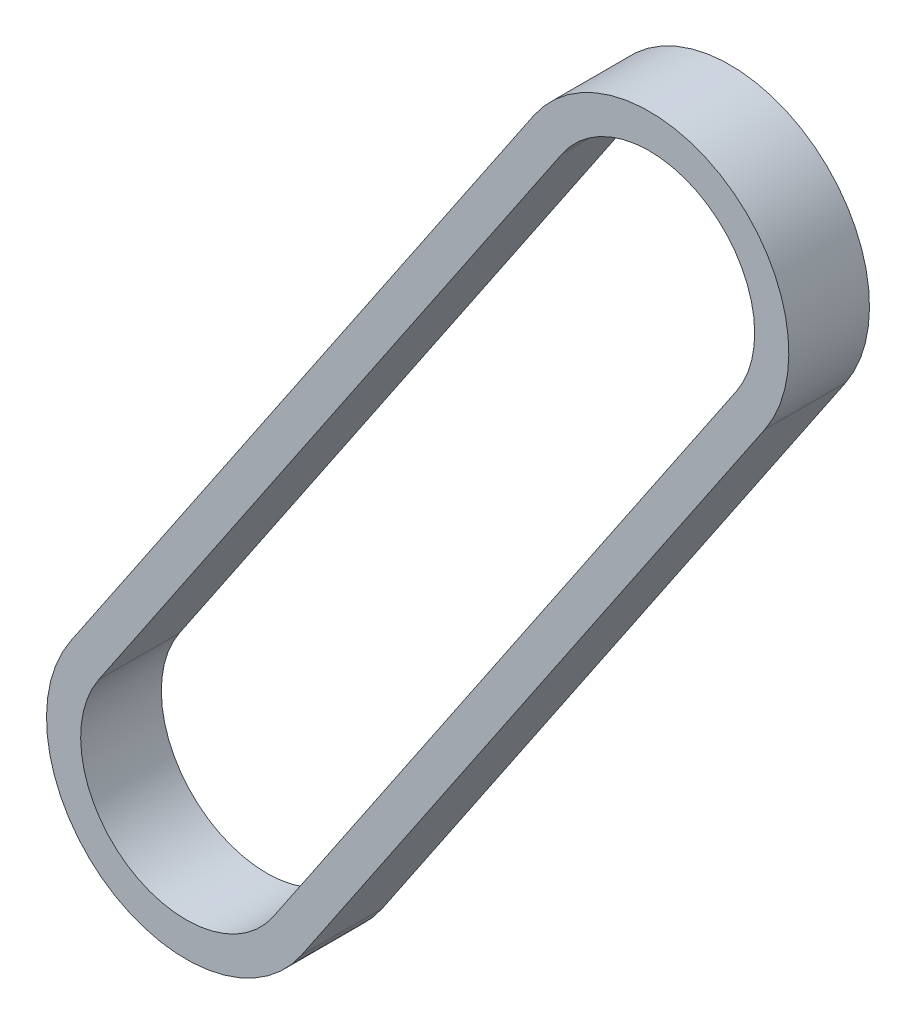
SolidWorks part; units mm, degrees
ref_plane "Front Plane" through (0, 0, 0) normal (0, 0, 1) x (1, 0, 0)
ref_plane "Top Plane" through (0, 0, 0) normal (0, 1, 0) x (1, 0, 0)
ref_plane "Right Plane" through (0, 0, 0) normal (1, 0, 0) x (0, 0, -1)
sketch "Sketch2" plane through (0, 0, 0) normal (0, 0, 1) x (1, 0, 0)
  line L0 (0, 0) -> (1, 0) construction
  line L1 (0, 0) -> (0, 1) construction
  line L2 (-63.158, -68.898) -> (-11.4682, 7.7354)
  line L3 (11.4682, -7.7354) -> (-40.2217, -84.3687)
  arc A0 (-40.2217, -84.3687) -> (-63.158, -68.898) centre (-51.6898, -76.6333) cw
  arc A1 (-11.4682, 7.7354) -> (11.4682, -7.7354) centre (0, 0) cw
extrude "Extrude-Thin1" add sketch "Sketch2" along normal mid plane 9 thin thin type two direction wall 1.73 second wall 2.08
equation "\"D1@Extrude-Thin1\"=9mm"
equation "\"D5@Extrude-Thin1\"=1.73mm"
equation "\"D6@Extrude-Thin1\"=2.08mm"
